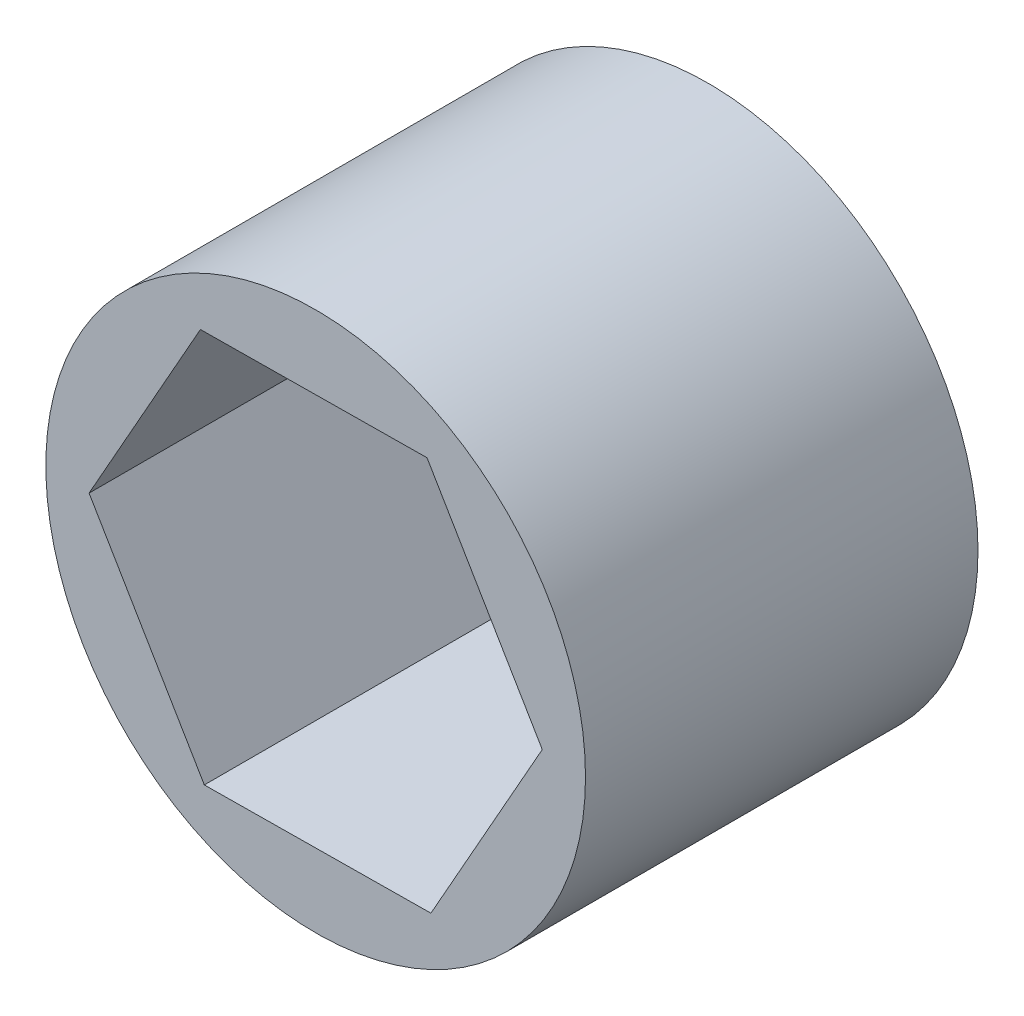
SolidWorks part; units mm, degrees
ref_plane "Front Plane" through (0, 0, 0) normal (0, 0, 1) x (1, 0, 0)
ref_plane "Top Plane" through (0, 0, 0) normal (0, 1, 0) x (1, 0, 0)
ref_plane "Right Plane" through (0, 0, 0) normal (1, 0, 0) x (0, 0, -1)
sketch "Sketch1" plane through (0, 0, 0) normal (0, 0, 1) x (1, 0, 0)
  circle A0 centre (0, 0) radius 8.7312
  dimension "D1" = 17.4625
extrude "Boss-Extrude1" add sketch "Sketch1" along normal blind 12.7
sketch "Sketch2" plane through (0, 0, 12.7) normal (0, 0, 1) x (1, 0, 0)
  line L1 (3.7289, -6.3134) -> (7.332, 0.0727)
  line L2 (7.332, 0.0727) -> (3.6031, 6.386)
  line L3 (3.6031, 6.386) -> (-3.7289, 6.3134)
  line L4 (-3.7289, 6.3134) -> (-7.332, -0.0727)
  line L5 (-7.332, -0.0727) -> (-3.6031, -6.386)
  line L6 (-3.6031, -6.386) -> (3.7289, -6.3134)
  circle A0 centre (0, 0) radius 6.35 construction
  dimension "D1" = 12.7
extrude "Cut-Extrude1" cut sketch "Sketch2" against normal through all
